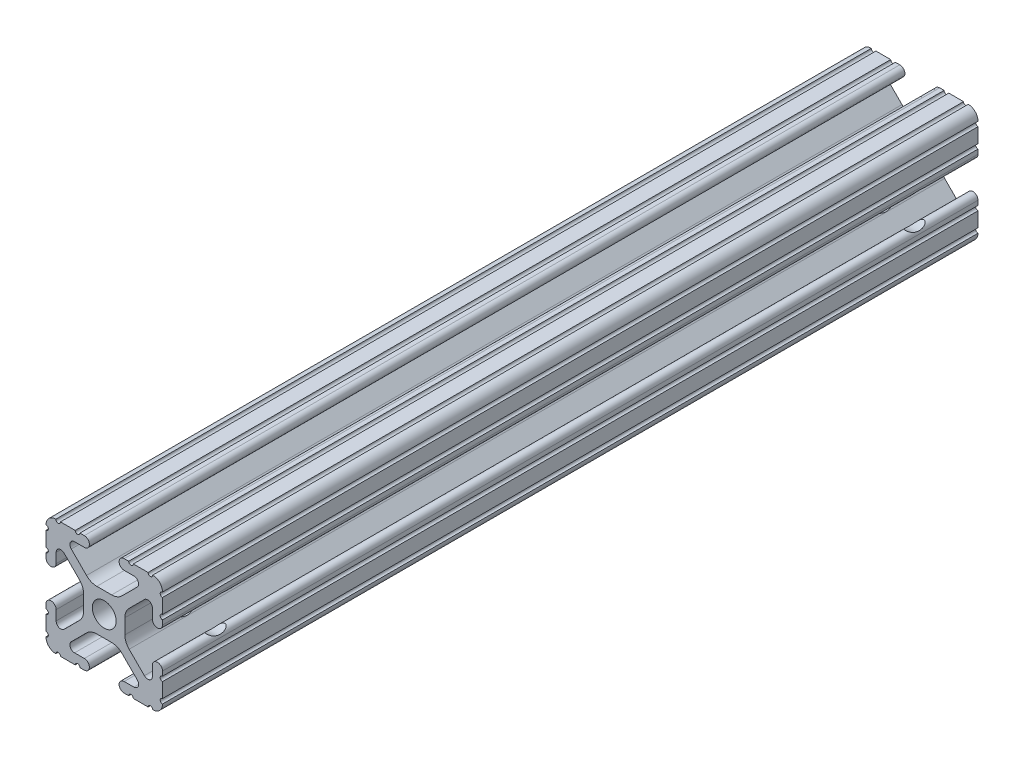
SolidWorks part; units mm, degrees
ref_plane "Front Plane" through (0, 0, 0) normal (0, 0, 1) x (1, 0, 0)
ref_plane "Top Plane" through (0, 0, 0) normal (0, 1, 0) x (1, 0, 0)
ref_plane "Right Plane" through (0, 0, 0) normal (1, 0, 0) x (0, 0, -1)
ref_plane "Plane1" through (0, 0, -25.4) normal (0, 0, -1) x (-1, 0, 0)
sketch "Sketch1" plane through (0, 0, -25.4) normal (0, 0, -1) x (-1, 0, 0)
  line L0 (12.7, -9.5504) -> (12.7, -6.3331)
  line L1 (12.7, -5.3171) -> (12.7, -4.3434)
  line L2 (10.4902, -4.3434) -> (10.4902, -6.4748)
  line L3 (8.7558, -7.1932) -> (5.4257, -3.8632)
  line L4 (4.4958, -1.6181) -> (4.4958, 1.6181)
  line L5 (5.4257, 3.8632) -> (8.7558, 7.1932)
  line L6 (10.4902, 6.4748) -> (10.4902, 4.3434)
  line L7 (12.7, 4.3434) -> (12.7, 5.3171)
  line L8 (12.7, 6.3331) -> (12.7, 9.5504)
  line L9 (9.5504, 12.7) -> (6.3331, 12.7)
  line L10 (5.3171, 12.7) -> (4.3434, 12.7)
  line L11 (4.3434, 10.4902) -> (6.4748, 10.4902)
  line L12 (7.1932, 8.7558) -> (3.8632, 5.4257)
  line L13 (1.6181, 4.4958) -> (-1.6181, 4.4958)
  line L14 (-3.8632, 5.4257) -> (-7.1932, 8.7558)
  line L15 (-6.4748, 10.4902) -> (-4.3434, 10.4902)
  line L16 (-4.3434, 12.7) -> (-5.3171, 12.7)
  line L17 (-6.3331, 12.7) -> (-9.5504, 12.7)
  line L18 (-12.7, 9.5504) -> (-12.7, 6.3331)
  line L19 (-12.7, 5.3171) -> (-12.7, 4.3434)
  line L20 (-10.4902, 4.3434) -> (-10.4902, 6.4748)
  line L21 (-8.7558, 7.1932) -> (-5.4257, 3.8632)
  line L22 (-4.4958, 1.6181) -> (-4.4958, -1.6181)
  line L23 (-5.4257, -3.8632) -> (-8.7558, -7.1932)
  line L24 (-10.4902, -6.4748) -> (-10.4902, -4.3434)
  line L25 (-12.7, -4.3434) -> (-12.7, -5.3171)
  line L26 (-12.7, -6.3331) -> (-12.7, -9.5504)
  line L27 (-9.5504, -12.7) -> (-6.3331, -12.7)
  line L28 (-5.3171, -12.7) -> (-4.3434, -12.7)
  line L29 (-4.3434, -10.4902) -> (-6.4748, -10.4902)
  line L30 (-7.1932, -8.7558) -> (-3.8632, -5.4257)
  line L31 (-1.6181, -4.4958) -> (1.6181, -4.4958)
  line L32 (3.8632, -5.4257) -> (7.1932, -8.7558)
  line L33 (6.4748, -10.4902) -> (4.3434, -10.4902)
  line L34 (4.3434, -12.7) -> (5.3171, -12.7)
  line L35 (6.3331, -12.7) -> (9.5504, -12.7)
  arc A0 (12.6998, -10.5664) -> (12.7, -9.5504) centre (12.7, -10.0584) cw
  arc A1 (12.7, -6.3331) -> (12.7, -5.3171) centre (12.7, -5.8251) cw
  arc A2 (12.7, -4.3434) -> (10.4902, -4.3434) centre (11.5951, -4.3434) ccw
  arc A3 (10.4902, -6.4748) -> (8.7558, -7.1932) centre (9.4742, -6.4748) cw
  arc A4 (5.4257, -3.8632) -> (4.4958, -1.6181) centre (7.6708, -1.6181) cw
  arc A5 (4.4958, 1.6181) -> (5.4257, 3.8632) centre (7.6708, 1.6181) cw
  arc A6 (8.7558, 7.1932) -> (10.4902, 6.4748) centre (9.4742, 6.4748) cw
  arc A7 (10.4902, 4.3434) -> (12.7, 4.3434) centre (11.5951, 4.3434) ccw
  arc A8 (12.7, 5.3171) -> (12.7, 6.3331) centre (12.7, 5.8251) cw
  arc A9 (12.7, 9.5504) -> (12.6998, 10.5664) centre (12.7, 10.0584) cw
  arc A10 (12.6998, 10.5664) -> (10.5664, 12.6998) centre (10.5918, 10.5918) ccw
  arc A11 (10.5664, 12.6998) -> (9.5504, 12.7) centre (10.0584, 12.7) cw
  arc A12 (6.3331, 12.7) -> (5.3171, 12.7) centre (5.8251, 12.7) cw
  arc A13 (4.3434, 12.7) -> (4.3434, 10.4902) centre (4.3434, 11.5951) ccw
  arc A14 (6.4748, 10.4902) -> (7.1932, 8.7558) centre (6.4748, 9.4742) cw
  arc A15 (3.8632, 5.4257) -> (1.6181, 4.4958) centre (1.6181, 7.6708) cw
  arc A16 (-1.6181, 4.4958) -> (-3.8632, 5.4257) centre (-1.6181, 7.6708) cw
  arc A17 (-7.1932, 8.7558) -> (-6.4748, 10.4902) centre (-6.4748, 9.4742) cw
  arc A18 (-4.3434, 10.4902) -> (-4.3434, 12.7) centre (-4.3434, 11.5951) ccw
  arc A19 (-5.3171, 12.7) -> (-6.3331, 12.7) centre (-5.8251, 12.7) cw
  arc A20 (-9.5504, 12.7) -> (-10.5664, 12.6998) centre (-10.0584, 12.7) cw
  arc A21 (-10.5664, 12.6998) -> (-12.6998, 10.5664) centre (-10.5918, 10.5918) ccw
  arc A22 (-12.6998, 10.5664) -> (-12.7, 9.5504) centre (-12.7, 10.0584) cw
  arc A23 (-12.7, 6.3331) -> (-12.7, 5.3171) centre (-12.7, 5.8251) cw
  arc A24 (-12.7, 4.3434) -> (-10.4902, 4.3434) centre (-11.5951, 4.3434) ccw
  arc A25 (-10.4902, 6.4748) -> (-8.7558, 7.1932) centre (-9.4742, 6.4748) cw
  arc A26 (-5.4257, 3.8632) -> (-4.4958, 1.6181) centre (-7.6708, 1.6181) cw
  arc A27 (-4.4958, -1.6181) -> (-5.4257, -3.8632) centre (-7.6708, -1.6181) cw
  arc A28 (-8.7558, -7.1932) -> (-10.4902, -6.4748) centre (-9.4742, -6.4748) cw
  arc A29 (-10.4902, -4.3434) -> (-12.7, -4.3434) centre (-11.5951, -4.3434) ccw
  arc A30 (-12.7, -5.3171) -> (-12.7, -6.3331) centre (-12.7, -5.8251) cw
  arc A31 (-12.7, -9.5504) -> (-12.6998, -10.5664) centre (-12.7, -10.0584) cw
  arc A32 (-12.6998, -10.5664) -> (-10.5664, -12.6998) centre (-10.5918, -10.5918) ccw
  arc A33 (-10.5664, -12.6998) -> (-9.5504, -12.7) centre (-10.0584, -12.7) cw
  arc A34 (-6.3331, -12.7) -> (-5.3171, -12.7) centre (-5.8251, -12.7) cw
  arc A35 (-4.3434, -12.7) -> (-4.3434, -10.4902) centre (-4.3434, -11.5951) ccw
  arc A36 (-6.4748, -10.4902) -> (-7.1932, -8.7558) centre (-6.4748, -9.4742) cw
  arc A37 (-3.8632, -5.4257) -> (-1.6181, -4.4958) centre (-1.6181, -7.6708) cw
  arc A38 (1.6181, -4.4958) -> (3.8632, -5.4257) centre (1.6181, -7.6708) cw
  arc A39 (7.1932, -8.7558) -> (6.4748, -10.4902) centre (6.4748, -9.4742) cw
  arc A40 (4.3434, -10.4902) -> (4.3434, -12.7) centre (4.3434, -11.5951) ccw
  arc A41 (5.3171, -12.7) -> (6.3331, -12.7) centre (5.8251, -12.7) cw
  arc A42 (9.5504, -12.7) -> (10.5664, -12.6998) centre (10.0584, -12.7) cw
  arc A43 (10.5664, -12.6998) -> (12.6998, -10.5664) centre (10.5918, -10.5918) ccw
  circle A44 centre (0, 0) radius 2.6035
extrude "Boss-Extrude1" add sketch "Sketch1" along normal blind 177.8
sketch "Sketch3" plane through (12.7, 0, 0) normal (1, 0, 0) x (0, 0, -1)
  line L0 (25.4, 1.6181) -> (25.4, -1.6181) construction
  line L1 (203.2, 12.6998) -> (25.4, 12.6998) construction
  line L2 (203.2, 0) -> (25.4, 0) construction
  line L3 (203.2, 1.6181) -> (203.2, -1.6181) construction
  line L4 (25.4, 0) -> (114.3, 0) construction
  line L5 (114.3, 0) -> (114.3, 36.2046) construction
  circle A0 centre (38.0998, 0) radius 3.81
  circle A1 centre (190.5002, 0) radius 3.81
  dimension "D1" = 7.62
  dimension "D2" = 12.6998
  dimension "D3" = 12.6998
extrude "Cut-Extrude1" cut sketch "Sketch3" against normal up to surface (25.4 mm away) up to face at (-12.7, 7.9417, -114.3)
